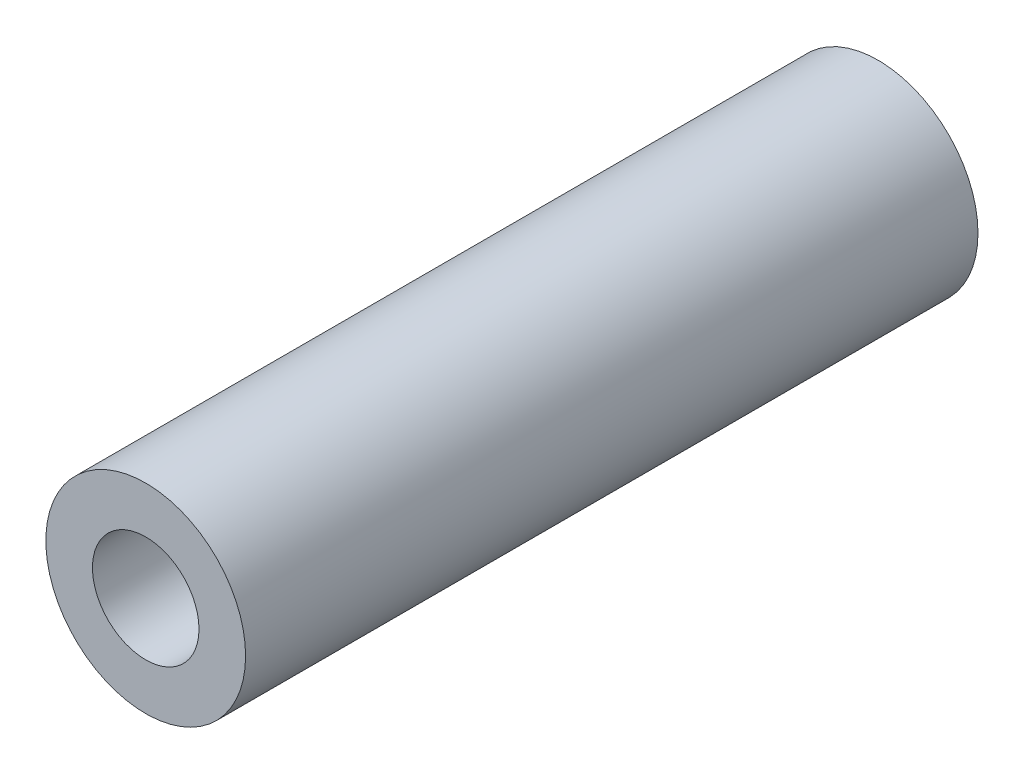
SolidWorks part; units mm, degrees
ref_plane "Front Plane" through (0, 0, 0) normal (0, 0, 1) x (1, 0, 0)
ref_plane "Top Plane" through (0, 0, 0) normal (0, 1, 0) x (1, 0, 0)
ref_plane "Right Plane" through (0, 0, 0) normal (1, 0, 0) x (0, 0, -1)
sketch "Sketch1" plane through (0, 0, 0) normal (0, 0, 1) x (1, 0, 0)
  circle A0 centre (0, 0) radius 8
  circle A1 centre (0, 0) radius 15
  dimension "D1" = 16
  dimension "D2" = 30
extrude "Boss-Extrude1" add sketch "Sketch1" along normal blind 110
